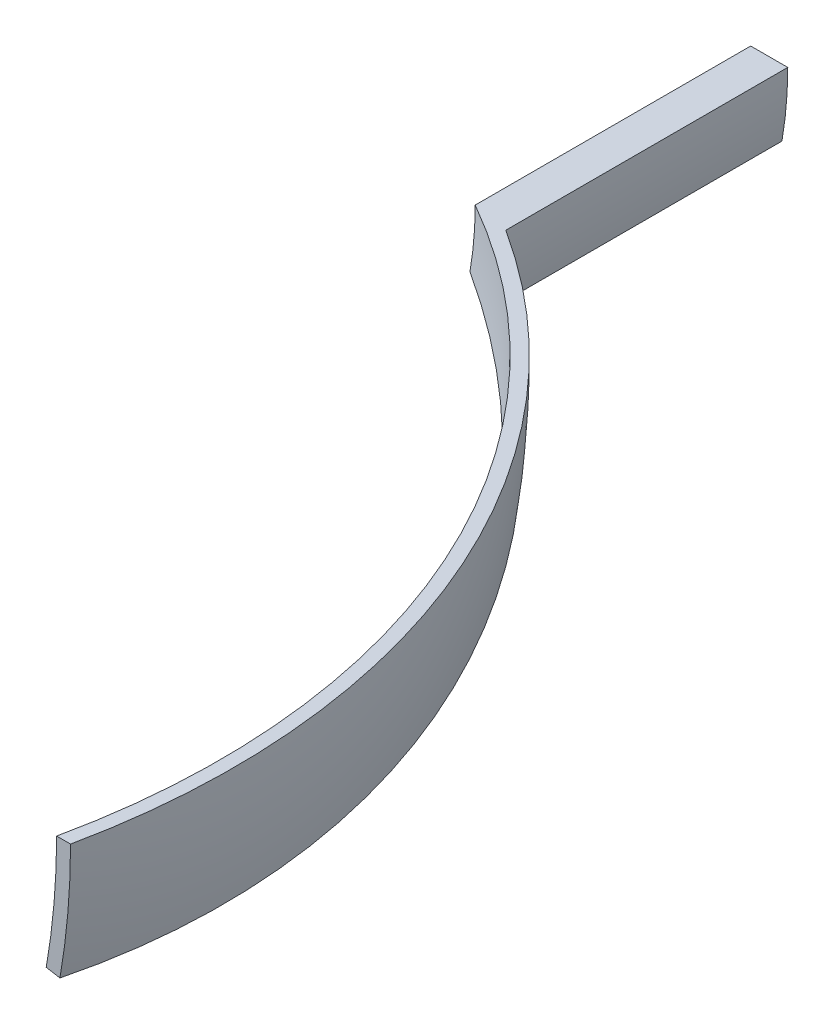
SolidWorks part; units mm, degrees
ref_plane "Front Plane" through (0, 0, 0) normal (0, 0, 1) x (1, 0, 0)
ref_plane "Top Plane" through (0, 0, 0) normal (0, 1, 0) x (1, 0, 0)
ref_plane "Right Plane" through (0, 0, 0) normal (1, 0, 0) x (0, 0, -1)
sketch "Sketch1" plane through (0, 0, 0) normal (0, 1, 0) x (1, 0, 0)
  line L0 (75, 190.7) -> (83, 190.7)
  line L1 (83, 190.7) -> (83, 129.8337)
  line L2 (75, 190.7) -> (75, 131.2448)
  line L3 (147.7666, -31.8623) -> (150.7666, -31.8623)
  line L4 (0, -125) -> (0, 125) construction
  arc A0 (83, 129.8337) -> (150.7666, -31.8623) centre (0, 0) cw
  arc A2 (75, 131.2448) -> (147.7666, -31.8623) centre (0, 0) cw
  point P8 (0, 0)
  point P12 (0, 0)
  dimension "D2" = 75
  dimension "D3" = 8
  dimension "D4" = 3
  dimension "D5" = 190.7
revolve "Revolve1" add sketch "Sketch1" angle 10 about L4
